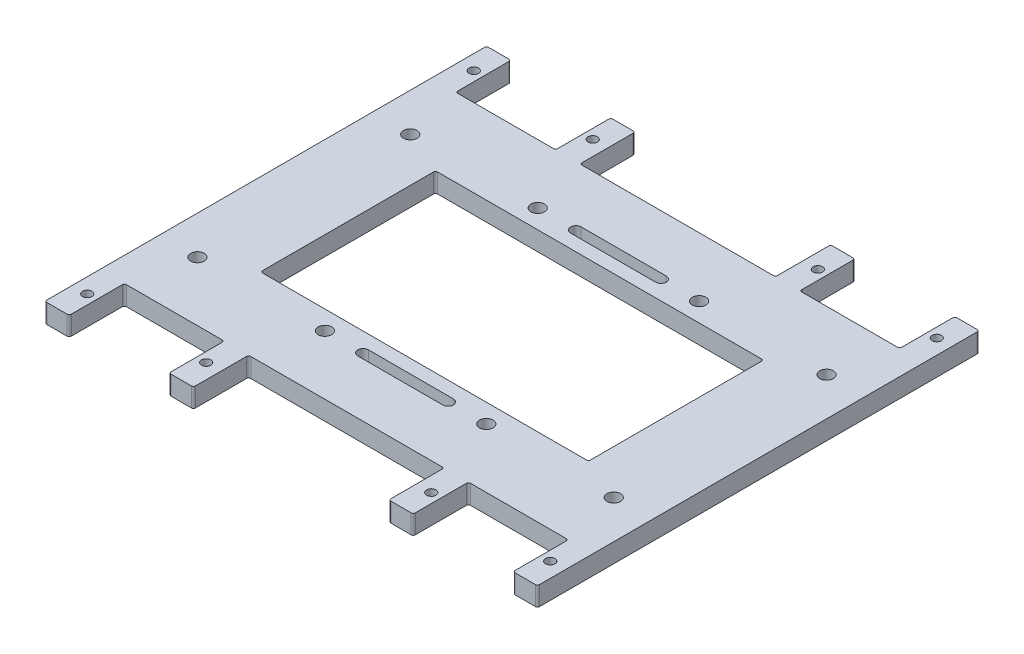
SolidWorks part; units mm, degrees
ref_plane "前视基准面" through (0, 0, 0) normal (0, 0, 1) x (1, 0, 0)
ref_plane "上视基准面" through (0, 0, 0) normal (0, 1, 0) x (1, 0, 0)
ref_plane "右视基准面" through (0, 0, 0) normal (1, 0, 0) x (0, 0, -1)
other "Configuration Table"
sketch "草图1" plane through (0, 0, 0) normal (0, 1, 0) x (1, 0, 0)
  line L0 (-58, -39) -> (-58, -52)
  line L2 (-58, 39) -> (-58, -39)
  line L4 (58, 39) -> (58, -39)
  line L5 (-58, 39) -> (58, -39) construction
  line L6 (-58, -39) -> (58, 39) construction
  line L15 (-78.7463, 0) -> (58.6748, 0) construction
  line L50 (-58, -52) -> (-52.25, -52)
  line L53 (-52.25, -52) -> (-52.25, -39)
  line L54 (-52.25, -39) -> (-28.75, -39)
  line L55 (-28.75, -39) -> (-28.75, -52)
  line L56 (-28.75, -52) -> (-23, -52)
  line L57 (-23, -52) -> (-23, -39)
  line L58 (-23, -39) -> (23, -39)
  line L59 (0, -1000) -> (0, 49000) construction
  line L60 (23, -52) -> (23, -39)
  line L61 (28.75, -52) -> (23, -52)
  line L62 (28.75, -39) -> (28.75, -52)
  line L63 (52.25, -39) -> (28.75, -39)
  line L64 (52.25, -52) -> (52.25, -39)
  line L65 (58, -52) -> (52.25, -52)
  line L66 (58, -39) -> (58, -52)
  line L67 (52.25, 39) -> (28.75, 39)
  line L68 (-23, 39) -> (23, 39)
  line L69 (-52.25, 39) -> (-28.75, 39)
  line L70 (0, 1000) -> (0, -49000) construction
  line L71 (58, 39) -> (58, 52)
  line L72 (58, 52) -> (52.25, 52)
  line L73 (52.25, 52) -> (52.25, 39)
  line L74 (28.75, 39) -> (28.75, 52)
  line L75 (28.75, 52) -> (23, 52)
  line L76 (23, 52) -> (23, 39)
  line L77 (-23, 52) -> (-23, 39)
  line L78 (-28.75, 52) -> (-23, 52)
  line L79 (-28.75, 39) -> (-28.75, 52)
  line L80 (-52.25, 52) -> (-52.25, 39)
  line L81 (-58, 52) -> (-52.25, 52)
  line L82 (-58, 39) -> (-58, 52)
  point P0 (0, 0)
  point P19 (0, -39)
  dimension "D8" = 23.5
  dimension "D10" = 23
  dimension "D2" = 78
  dimension "D3" = 13
  dimension "D4" = 13
  dimension "D5" = 13
  dimension "D6" = 13
  dimension "D7" = 5.75
  dimension "D9" = 5.75
extrude "凸台-拉伸1" add sketch "草图1" against normal blind 4.5
sketch "草图10" plane through (0, 0, 0) normal (0, 1, 0) x (1, 0, 0)
  line L5 (38.6, 20.6) -> (-38.6, 20.6)
  line L6 (38.6, 20.6) -> (38.6, -20.6)
  line L7 (38.6, -20.6) -> (-38.6, -20.6)
  line L8 (-38.6, 20.6) -> (-38.6, -20.6)
  line L9 (38.6, 20.6) -> (-38.6, -20.6) construction
  line L10 (38.6, -20.6) -> (-38.6, 20.6) construction
  point P0 (0, 0)
  dimension "D1" = 77.2
  dimension "D2" = 41.2
extrude "切除-拉伸5" cut sketch "草图10" against normal through all
sketch "草图16" plane through (0, 0, 0) normal (0, 1, 0) x (1, 0, 0)
  line L0 (-10, 25.05) -> (10, 25.05) construction
  line L1 (-10, 26.3) -> (10, 26.3)
  line L2 (-10, 23.8) -> (10, 23.8)
  line L3 (-1000, 0) -> (49000, 0) construction
  line L4 (0, -1000) -> (0, 49000) construction
  line L6 (-10, -25.05) -> (10, -25.05) construction
  line L7 (-10, -26.3) -> (10, -26.3)
  line L8 (-10, -23.8) -> (10, -23.8)
  arc A0 (-10, 26.3) -> (-10, 23.8) centre (-10, 25.05) ccw
  arc A1 (10, 23.8) -> (10, 26.3) centre (10, 25.05) ccw
  arc A2 (-10, -26.3) -> (-10, -23.8) centre (-10, -25.05) cw
  arc A3 (10, -23.8) -> (10, -26.3) centre (10, -25.05) cw
  circle A4 centre (19, 25.05) radius 1.6
  circle A5 centre (49, 25.05) radius 1.6
  circle A6 centre (-49, 25.05) radius 1.6
  circle A7 centre (-19, 25.05) radius 1.6
  circle A8 centre (49, -25.05) radius 1.6
  circle A9 centre (19, -25.05) radius 1.6
  circle A10 centre (-19, -25.05) radius 1.6
  circle A11 centre (-49, -25.05) radius 1.6
  point P2 (0, 25.05)
  point P17 (0, -25.05)
  dimension "D4" = 3.2
  dimension "D5" = 3.2
  dimension "D1" = 2.5
  dimension "D2" = 20
  dimension "D7" = 9
  dimension "D8" = 30
extrude "切除-拉伸6" cut sketch "草图16" against normal blind 10
sketch "草图17" plane through (0, 0, 0) normal (0, 1, 0) x (1, 0, 0)
  line L0 (-52.25, -39) -> (-28.75, -39) construction
  line L1 (-52.25, -52) -> (-52.25, -39) construction
  line L2 (-28.75, -39) -> (-28.75, -52) construction
  line L3 (-1000, 0) -> (49000, 0) construction
  line L4 (0, -1000) -> (0, 49000) construction
  circle A0 centre (-54.5, -45.5) radius 1.1
  circle A1 centre (-26.5, -45.5) radius 1.1
  circle A2 centre (26.5, -45.5) radius 1.1
  circle A3 centre (54.5, -45.5) radius 1.1
  circle A4 centre (54.5, 45.5) radius 1.1
  circle A5 centre (-26.5, 45.5) radius 1.1
  circle A6 centre (-54.5, 45.5) radius 1.1
  circle A7 centre (26.5, 45.5) radius 1.1
  point P21 (26.5, 45.5)
  dimension "D3" = 2.2
  dimension "D4" = 2.2
  dimension "D1" = 6.5
  dimension "D2" = 2.25
  dimension "D5" = 6.5
  dimension "D6" = 2.25
extrude "切除-拉伸7" cut sketch "草图17" against normal blind 10
fillet "圆角1" radius 0.5 32 edges at (52.25, -2.25, -39) (28.75, -2.25, -39) (23, -2.25, -39) (-23, -2.25, -39) (-28.75, -2.25, -39) (-52.25, -2.25, -39) (-52.25, -2.25, 52) (-52.25, -2.25, 39) (-28.75, -2.25, 39) (-28.75, -2.25, 52) (-23, -2.25, 52) (-23, -2.25, 39) (23, -2.25, 39) (23, -2.25, 52) (28.75, -2.25, 52) (28.75, -2.25, 39) (52.25, -2.25, 39) (52.25, -2.25, 52) (58, -2.25, 52) (-38.6, -2.25, -20.6) (38.6, -2.25, -20.6) (38.6, -2.25, 20.6) (-38.6, -2.25, 20.6) (-58, -2.25, 52) (58, -2.25, -52) (52.25, -2.25, -52) (28.75, -2.25, -52) (23, -2.25, -52) (-23, -2.25, -52) (-28.75, -2.25, -52) (-52.25, -2.25, -52) (-58, -2.25, -52)
